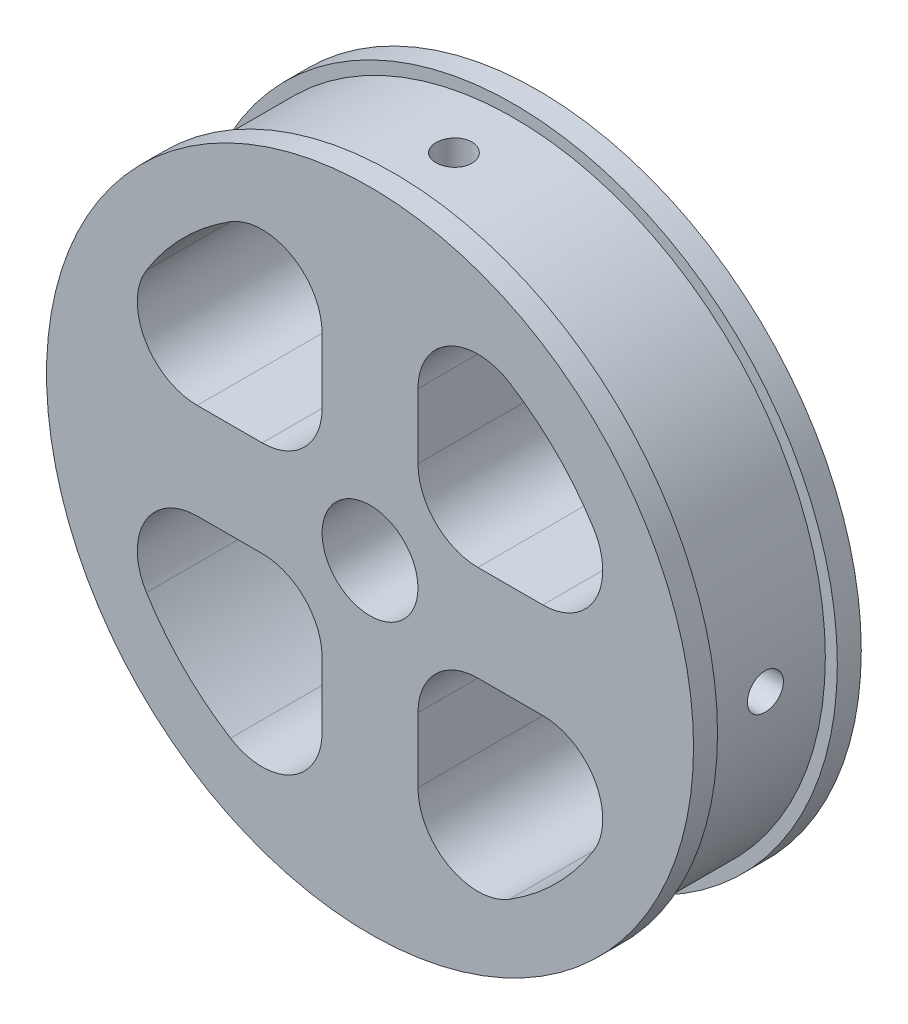
SolidWorks part; units mm, degrees
ref_plane "Plan de face" through (0, 0, 0) normal (0, 0, 1) x (1, 0, 0)
ref_plane "Plan de dessus" through (0, 0, 0) normal (0, 1, 0) x (1, 0, 0)
ref_plane "Plan de droite" through (0, 0, 0) normal (1, 0, 0) x (0, 0, -1)
sketch "Esquisse1" plane through (0, 0, 0) normal (0, 0, 1) x (1, 0, 0)
  circle A0 centre (0, 0) radius 27
extrude "Boss.-Extru.1" add sketch "Esquisse1" along normal blind 2
sketch "Esquisse2" plane through (0, 0, 2) normal (0, 0, 1) x (1, 0, 0)
  circle A0 centre (0, 0) radius 26
extrude "Boss.-Extru.2" add sketch "Esquisse2" along normal blind 10
sketch "Esquisse3" plane through (0, 0, 12) normal (0, 0, 1) x (1, 0, 0)
  circle A0 centre (0, 0) radius 27
extrude "Boss.-Extru.3" add sketch "Esquisse3" along normal blind 2
sketch "Esquisse4" plane through (0, 0, 14) normal (0, 0, 1) x (1, 0, 0)
  circle A0 centre (0, 0) radius 4
extrude "Enlèv. mat.-Extru.1" cut sketch "Esquisse4" against normal through all
sketch "Esquisse5" plane through (0, 0, 14) normal (0, 0, 1) x (1, 0, 0)
  line L0 (-4, 14.4222) -> (-4, 9)
  line L2 (-9, 4) -> (-14.4222, 4)
  line L4 (4, 14.4222) -> (4, 9)
  line L6 (9, 4) -> (14.4222, 4)
  line L8 (14.4222, -4) -> (9, -4)
  line L10 (4, -9) -> (4, -14.4222)
  line L12 (-4, -9) -> (-4, -14.4222)
  line L14 (-14.4222, -4) -> (-9, -4)
  arc A0 (-18.664, -11.6471) -> (-11.6471, -18.664) centre (0, 0) ccw
  arc A1 (-18.664, 11.6471) -> (-11.6471, 18.664) centre (0, 0) cw
  arc A2 (11.6471, 18.664) -> (18.664, 11.6471) centre (0, 0) cw
  arc A3 (11.6471, -18.664) -> (18.664, -11.6471) centre (0, 0) ccw
  arc A4 (-18.664, -11.6471) -> (-14.4222, -4) centre (-14.4222, -9) cw
  arc A5 (-11.6471, -18.664) -> (-4, -14.4222) centre (-9, -14.4222) ccw
  arc A6 (-9, -4) -> (-4, -9) centre (-9, -9) cw
  arc A7 (-5.5514, 4) -> (-4, 5.5514) centre (0, 0) ccw construction
  arc A8 (4, -9) -> (9, -4) centre (9, -9) cw
  arc A9 (4, -14.4222) -> (11.6471, -18.664) centre (9, -14.4222) ccw
  arc A10 (14.4222, -4) -> (18.664, -11.6471) centre (14.4222, -9) cw
  arc A11 (14.4222, 4) -> (18.664, 11.6471) centre (14.4222, 9) ccw
  arc A12 (4, 9) -> (9, 4) centre (9, 9) ccw
  arc A13 (-9, 4) -> (-4, 9) centre (-9, 9) ccw
  arc A14 (-18.664, 11.6471) -> (-14.4222, 4) centre (-14.4222, 9) ccw
  arc A15 (-11.6471, 18.664) -> (-4, 14.4222) centre (-9, 14.4222) cw
  arc A16 (4, 14.4222) -> (11.6471, 18.664) centre (9, 14.4222) cw
  dimension "D14" = 5
  dimension "D4" = 4
  dimension "D8" = 4
  dimension "D9" = 22
  dimension "D10" = 22
  dimension "D11" = 22
  dimension "D12" = 22
  dimension "D13" = 5
  dimension "D15" = 5
  dimension "D16" = 5
  dimension "D17" = 5
  dimension "D18" = 5
  dimension "D19" = 5
  dimension "D20" = 5
  dimension "D21" = 5
  dimension "D22" = 5
  dimension "D23" = 5
  dimension "D24" = 5
  dimension "D1" = 8
  dimension "D2" = 8
  dimension "D3" = 8
  dimension "D5" = 8
  dimension "D6" = 4
  dimension "D7" = 4
extrude "Enlèv. mat.-Extru.2" cut sketch "Esquisse5" against normal through all
ref_plane "Plan1" through (0, 26, 0) normal (0, 1, 0) x (-1, 0, 0)
sketch "Esquisse6" plane through (0, 26, 0) normal (0, 1, 0) x (-1, 0, 0)
  line L0 (-27, 0) -> (27, 0) construction
  circle A0 centre (0, 7) radius 1.5
  dimension "D1" = 7
extrude "Enlèv. mat.-Extru.3" cut sketch "Esquisse6" against normal through all
ref_plane "Plan2" through (-26, 0, 0) normal (-1, 0, 0) x (0, 0, 1)
sketch "Esquisse7" plane through (-26, 0, 0) normal (-1, 0, 0) x (0, 0, 1)
  circle A0 centre (7, 0) radius 1.5
  dimension "D1" = 7
extrude "Enlèv. mat.-Extru.4" cut sketch "Esquisse7" against normal through all
